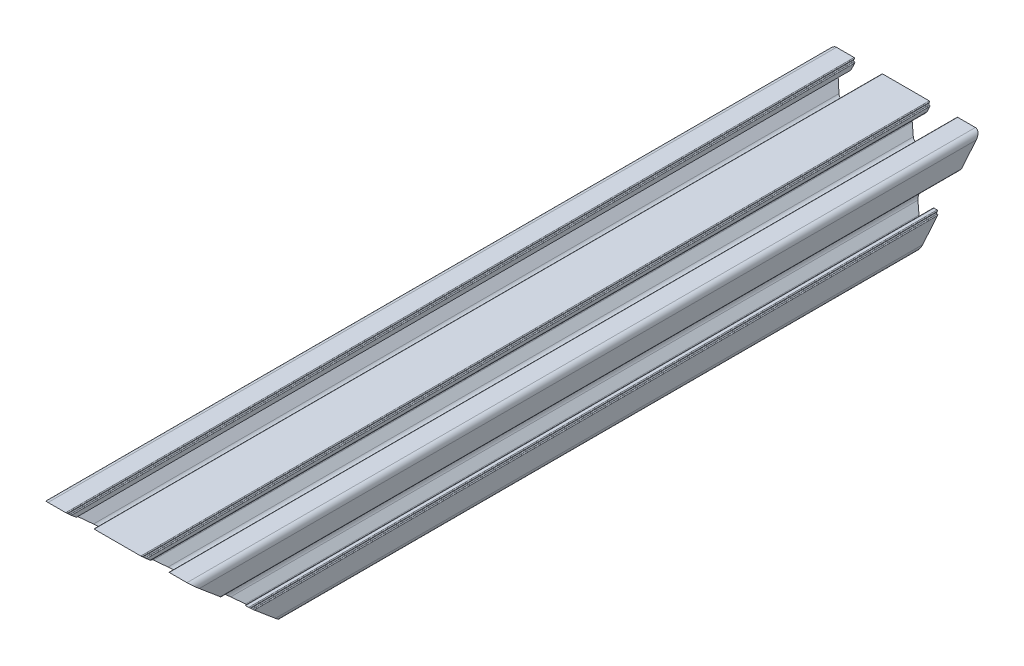
SolidWorks part; units mm, degrees
material "6063-O"
ref_plane "Front Plane" through (0, 0, 0) normal (0, 0, 1) x (1, 0, 0)
ref_plane "Top Plane" through (0, 0, 0) normal (0, 1, 0) x (1, 0, 0)
ref_plane "Right Plane" through (0, 0, 0) normal (1, 0, 0) x (0, 0, -1)
sketch "Sketch1" plane through (0, 0, 0) normal (0, 0, 1) x (1, 0, 0)
  line L0 (1.5, 0) -> (6.2, 0)
  line L1 (40, 1.5) -> (40, 6.2)
  line L2 (38.5, 20) -> (33.8, 20)
  line L3 (0, 18.5) -> (0, 13.8)
  line L4 (17.6, 1.8) -> (22.4, 1.8)
  line L5 (32.218, 13.9) -> (27.782, 13.9)
  line L6 (26.1, 12.218) -> (26.1, 7.782)
  line L7 (17.6, 18.2) -> (22.4, 18.2)
  line L8 (12.218, 13.9) -> (7.9864, 13.9)
  line L9 (6.1, 12.218) -> (6.1, 7.782)
  line L10 (7.782, 6.1) -> (12.218, 6.1)
  line L11 (13.9, 7.782) -> (13.9, 12.218)
  line L12 (27.782, 6.1) -> (32.218, 6.1)
  line L13 (33.9, 7.782) -> (33.9, 12.218)
  line L14 (26.7213, 14.3393) -> (24.9393, 16.1213)
  line L15 (33.2787, 14.3393) -> (35.0607, 16.1213)
  line L16 (34.3393, 13.2787) -> (36.1213, 15.0607)
  line L17 (25.6607, 6.7213) -> (23.1393, 4.2)
  line L18 (15.2, 1.8) -> (13.4, 1.8)
  line L19 (26.7213, 5.6607) -> (24.9393, 3.8787)
  line L20 (24.8, 1.8) -> (26.6, 1.8)
  line L21 (15.3, 18.2) -> (13.1, 18.2)
  line L22 (13.2787, 14.3393) -> (15.1607, 16.2213)
  line L23 (14.3393, 13.2787) -> (16.8607, 15.8)
  line L24 (5.6607, 6.7213) -> (3.8787, 4.9393)
  line L25 (6.7213, 5.6607) -> (4.9393, 3.8787)
  line L26 (6.897, 14.3689) -> (4.9106, 16.4674)
  line L27 (5.6607, 13.2787) -> (3.8787, 15.0607)
  line L28 (14.3393, 6.7213) -> (16.8607, 4.2)
  line L29 (13.2787, 5.6607) -> (15.0607, 3.8787)
  line L30 (24.8, 18.2) -> (26.6, 18.2)
  line L31 (25.6607, 13.2787) -> (23.1393, 15.8)
  line L32 (34.3393, 6.7213) -> (36.1213, 4.9393)
  line L33 (33.2787, 5.6607) -> (35.0607, 3.8787)
  line L34 (1.8, 15.2) -> (1.8, 13.4)
  line L35 (24.5, 2.1) -> (24.5, 2.818)
  line L36 (4.5, 2.1) -> (4.5, 2.818)
  line L37 (2.818, 4.5) -> (2.1, 4.5)
  line L38 (4.5, 17.9) -> (4.5, 17.4986)
  line L39 (2.818, 15.5) -> (2.1, 15.5)
  line L40 (15.6, 17.9) -> (15.6, 17.282)
  line L41 (15.5, 2.818) -> (15.5, 2.1)
  line L42 (38.2, 15.2) -> (38.2, 13.4)
  line L43 (35.5, 2.818) -> (35.5, 2.1)
  line L44 (37.182, 4.5) -> (37.9, 4.5)
  line L45 (35.5, 17.182) -> (35.5, 17.9)
  line L46 (37.182, 15.5) -> (37.9, 15.5)
  line L47 (17.3, 2.1) -> (17.3, 3.1393)
  line L48 (22.7, 2.1) -> (22.7, 3.1393)
  line L49 (17.3, 17.9) -> (17.3, 16.8607)
  line L50 (22.7, 17.9) -> (22.7, 16.8607)
  line L51 (24.5, 17.9) -> (24.5, 17.182)
  line L52 (6.9, 19.3) -> (6.9, 18.2)
  line L53 (13.1, 19.3) -> (13.1, 18.2)
  line L54 (6.9, 1.5) -> (6.9, 0.7)
  line L55 (13.1, 1.5) -> (13.1, 0.7)
  line L56 (13.8, 0) -> (26.2, 0)
  line L57 (6.6, 1.8) -> (4.8, 1.8)
  line L58 (6.9, 18.2) -> (4.8, 18.2)
  line L59 (6.2, 20) -> (1.5, 20)
  line L60 (39.3, 6.9) -> (38.5, 6.9)
  line L61 (39.3, 13.1) -> (38.5, 13.1)
  line L62 (1.5, 13.1) -> (0.7, 13.1)
  line L63 (1.5, 6.9) -> (0.7, 6.9)
  line L64 (0, 6.2) -> (0, 1.5)
  line L65 (1.8, 6.6) -> (1.8, 4.8)
  line L66 (38.2, 6.6) -> (38.2, 4.8)
  line L67 (40, 13.8) -> (40, 18.5)
  line L68 (33.1, 19.3) -> (33.1, 18.5)
  line L69 (26.9, 19.3) -> (26.9, 18.5)
  line L70 (26.9, 1.5) -> (26.9, 0.7)
  line L71 (33.1, 1.5) -> (33.1, 0.7)
  line L72 (33.8, 0) -> (38.5, 0)
  line L73 (33.4, 1.8) -> (35.2, 1.8)
  line L74 (26.2, 20) -> (13.8, 20)
  line L75 (33.4, 18.2) -> (35.2, 18.2)
  line L76 (6.7, 0.5) -> (6.6, 0.5)
  line L77 (6.4, 0.3) -> (6.4, 0.2)
  line L78 (13.3, 0.5) -> (13.4, 0.5)
  line L79 (13.6, 0.3) -> (13.6, 0.2)
  line L80 (26.7, 0.5) -> (26.6, 0.5)
  line L81 (26.4, 0.3) -> (26.4, 0.2)
  line L82 (33.3, 0.5) -> (33.4, 0.5)
  line L83 (33.6, 0.3) -> (33.6, 0.2)
  line L85 (6.4, 19.8) -> (6.4, 19.7)
  line L86 (6.6, 19.5) -> (6.7, 19.5)
  line L87 (13.6, 19.8) -> (13.6, 19.7)
  line L88 (13.4, 19.5) -> (13.3, 19.5)
  line L89 (26.4, 19.8) -> (26.4, 19.7)
  line L90 (26.6, 19.5) -> (26.7, 19.5)
  line L91 (33.6, 19.8) -> (33.6, 19.7)
  line L92 (33.4, 19.5) -> (33.3, 19.5)
  line L93 (0.5, 13.3) -> (0.5, 13.4)
  line L94 (0.3, 13.6) -> (0.2, 13.6)
  line L95 (0.5, 6.7) -> (0.5, 6.6)
  line L96 (0.3, 6.4) -> (0.2, 6.4)
  line L97 (39.5, 13.3) -> (39.5, 13.4)
  line L98 (39.7, 13.6) -> (39.8, 13.6)
  line L99 (39.5, 6.7) -> (39.5, 6.6)
  line L100 (39.7, 6.4) -> (39.8, 6.4)
  circle A0 centre (10, 10) radius 2.5
  circle A1 centre (30, 10) radius 2.5
  arc A2 (38.5, 0) -> (40, 1.5) centre (38.5, 1.5) ccw
  arc A3 (40, 18.5) -> (38.5, 20) centre (38.5, 18.5) ccw
  arc A4 (1.5, 0) -> (0, 1.5) centre (1.5, 1.5) cw
  arc A5 (1.5, 20) -> (0, 18.5) centre (1.5, 18.5) ccw
  arc A6 (26.7213, 5.6607) -> (27.782, 6.1) centre (27.782, 4.6) cw
  arc A7 (32.218, 6.1) -> (33.2787, 5.6607) centre (32.218, 4.6) cw
  arc A8 (33.9, 7.782) -> (34.3393, 6.7213) centre (35.4, 7.782) ccw
  arc A9 (33.2787, 14.3393) -> (32.218, 13.9) centre (32.218, 15.4) cw
  arc A10 (14.3393, 6.7213) -> (13.9, 7.782) centre (15.4, 7.782) cw
  arc A11 (14.3393, 13.2787) -> (13.9, 12.218) centre (15.4, 12.218) ccw
  arc A12 (25.6607, 6.7213) -> (26.1, 7.782) centre (24.6, 7.782) ccw
  arc A13 (26.1, 12.218) -> (25.6607, 13.2787) centre (24.6, 12.218) ccw
  arc A14 (27.782, 13.9) -> (26.7213, 14.3393) centre (27.782, 15.4) cw
  arc A15 (5.6607, 13.2787) -> (6.1, 12.218) centre (4.6, 12.218) cw
  arc A16 (5.6607, 6.7213) -> (6.1, 7.782) centre (4.6, 7.782) ccw
  arc A17 (13.2787, 5.6607) -> (12.218, 6.1) centre (12.218, 4.6) ccw
  arc A18 (6.7213, 5.6607) -> (7.782, 6.1) centre (7.782, 4.6) cw
  arc A19 (13.2787, 14.3393) -> (12.218, 13.9) centre (12.218, 15.4) cw
  arc A20 (6.897, 14.3689) -> (7.9864, 13.9) centre (7.9864, 15.4) ccw
  arc A21 (36.1213, 4.9393) -> (37.182, 4.5) centre (37.182, 6) ccw
  arc A22 (36.1213, 15.0607) -> (37.182, 15.5) centre (37.182, 14) cw
  arc A23 (35.0607, 16.1213) -> (35.5, 17.182) centre (34, 17.182) ccw
  arc A24 (24.5, 17.182) -> (24.9393, 16.1213) centre (26, 17.182) ccw
  arc A25 (22.7, 16.8607) -> (23.1393, 15.8) centre (24.2, 16.8607) ccw
  arc A26 (17.3, 16.8607) -> (16.8607, 15.8) centre (15.8, 16.8607) cw
  arc A27 (4.9106, 16.4674) -> (4.5, 17.4986) centre (6, 17.4986) cw
  arc A28 (15.6, 17.282) -> (15.1607, 16.2213) centre (14.1, 17.282) cw
  arc A29 (3.8787, 15.0607) -> (2.818, 15.5) centre (2.818, 14) ccw
  arc A30 (3.8787, 4.9393) -> (2.818, 4.5) centre (2.818, 6) cw
  arc A31 (4.9393, 3.8787) -> (4.5, 2.818) centre (6, 2.818) ccw
  arc A32 (35.0607, 3.8787) -> (35.5, 2.818) centre (34, 2.818) cw
  arc A33 (24.9393, 3.8787) -> (24.5, 2.818) centre (26, 2.818) ccw
  arc A34 (22.7, 3.1393) -> (23.1393, 4.2) centre (24.2, 3.1393) cw
  arc A35 (17.3, 3.1393) -> (16.8607, 4.2) centre (15.8, 3.1393) ccw
  arc A36 (15.5, 2.818) -> (15.0607, 3.8787) centre (14, 2.818) ccw
  arc A37 (1.8, 6.6) -> (1.5, 6.9) centre (1.5, 6.6) ccw
  arc A38 (1.8, 13.4) -> (1.5, 13.1) centre (1.5, 13.4) cw
  arc A39 (17.6, 18.2) -> (17.3, 17.9) centre (17.6, 17.9) ccw
  arc A40 (22.4, 1.8) -> (22.7, 2.1) centre (22.4, 2.1) ccw
  arc A41 (17.6, 1.8) -> (17.3, 2.1) centre (17.6, 2.1) cw
  arc A42 (15.2, 1.8) -> (15.5, 2.1) centre (15.2, 2.1) ccw
  arc A43 (6.6, 1.8) -> (6.9, 1.5) centre (6.6, 1.5) cw
  arc A44 (13.4, 1.8) -> (13.1, 1.5) centre (13.4, 1.5) ccw
  arc A45 (24.8, 1.8) -> (24.5, 2.1) centre (24.8, 2.1) cw
  arc A46 (35.2, 1.8) -> (35.5, 2.1) centre (35.2, 2.1) ccw
  arc A47 (26.6, 1.8) -> (26.9, 1.5) centre (26.6, 1.5) cw
  arc A48 (33.4, 1.8) -> (33.1, 1.5) centre (33.4, 1.5) ccw
  arc A49 (26.9, 18.5) -> (26.6, 18.2) centre (26.6, 18.5) cw
  arc A50 (33.1, 18.5) -> (33.4, 18.2) centre (33.4, 18.5) ccw
  arc A51 (37.9, 4.5) -> (38.2, 4.8) centre (37.9, 4.8) ccw
  arc A52 (38.5, 13.1) -> (38.2, 13.4) centre (38.5, 13.4) cw
  arc A53 (38.5, 6.9) -> (38.2, 6.6) centre (38.5, 6.6) ccw
  arc A54 (38.2, 15.2) -> (37.9, 15.5) centre (37.9, 15.2) ccw
  arc A55 (35.2, 18.2) -> (35.5, 17.9) centre (35.2, 17.9) cw
  arc A56 (24.8, 18.2) -> (24.5, 17.9) centre (24.8, 17.9) ccw
  arc A57 (22.4, 18.2) -> (22.7, 17.9) centre (22.4, 17.9) cw
  arc A58 (15.3, 18.2) -> (15.6, 17.9) centre (15.3, 17.9) cw
  arc A59 (4.5, 17.9) -> (4.8, 18.2) centre (4.8, 17.9) cw
  arc A60 (1.8, 15.2) -> (2.1, 15.5) centre (2.1, 15.2) cw
  arc A61 (1.8, 4.8) -> (2.1, 4.5) centre (2.1, 4.8) ccw
  arc A62 (4.5, 2.1) -> (4.8, 1.8) centre (4.8, 2.1) ccw
  arc A63 (34.3393, 13.2787) -> (33.9, 12.218) centre (35.4, 12.218) ccw
  arc A64 (6.4, 0.2) -> (6.2, 0) centre (6.2, 0.2) cw
  arc A65 (6.6, 0.5) -> (6.4, 0.3) centre (6.6, 0.3) ccw
  arc A66 (6.7, 0.5) -> (6.9, 0.7) centre (6.7, 0.7) ccw
  arc A67 (13.6, 0.2) -> (13.8, 0) centre (13.8, 0.2) ccw
  arc A68 (13.4, 0.5) -> (13.6, 0.3) centre (13.4, 0.3) cw
  arc A69 (13.3, 0.5) -> (13.1, 0.7) centre (13.3, 0.7) cw
  arc A70 (26.4, 0.2) -> (26.2, 0) centre (26.2, 0.2) cw
  arc A71 (26.6, 0.5) -> (26.4, 0.3) centre (26.6, 0.3) ccw
  arc A72 (26.7, 0.5) -> (26.9, 0.7) centre (26.7, 0.7) ccw
  arc A73 (33.6, 0.2) -> (33.8, 0) centre (33.8, 0.2) ccw
  arc A74 (33.4, 0.5) -> (33.6, 0.3) centre (33.4, 0.3) cw
  arc A75 (33.3, 0.5) -> (33.1, 0.7) centre (33.3, 0.7) cw
  arc A76 (39.8, 6.4) -> (40, 6.2) centre (39.8, 6.2) cw
  arc A77 (39.5, 6.6) -> (39.7, 6.4) centre (39.7, 6.6) ccw
  arc A78 (39.5, 6.7) -> (39.3, 6.9) centre (39.3, 6.7) ccw
  arc A79 (39.5, 13.3) -> (39.3, 13.1) centre (39.3, 13.3) cw
  arc A80 (39.5, 13.4) -> (39.7, 13.6) centre (39.7, 13.4) cw
  arc A81 (39.8, 13.6) -> (40, 13.8) centre (39.8, 13.8) ccw
  arc A82 (33.3, 19.5) -> (33.1, 19.3) centre (33.3, 19.3) ccw
  arc A83 (33.6, 19.7) -> (33.4, 19.5) centre (33.4, 19.7) cw
  arc A84 (33.6, 19.8) -> (33.8, 20) centre (33.8, 19.8) cw
  arc A85 (26.7, 19.5) -> (26.9, 19.3) centre (26.7, 19.3) cw
  arc A86 (26.4, 19.7) -> (26.6, 19.5) centre (26.6, 19.7) ccw
  arc A87 (26.4, 19.8) -> (26.2, 20) centre (26.2, 19.8) ccw
  arc A88 (0.2, 6.4) -> (0, 6.2) centre (0.2, 6.2) ccw
  arc A89 (0.5, 6.6) -> (0.3, 6.4) centre (0.3, 6.6) cw
  arc A90 (0.5, 6.7) -> (0.7, 6.9) centre (0.7, 6.7) cw
  arc A91 (13.3, 19.5) -> (13.1, 19.3) centre (13.3, 19.3) ccw
  arc A92 (13.6, 19.7) -> (13.4, 19.5) centre (13.4, 19.7) cw
  arc A93 (13.6, 19.8) -> (13.8, 20) centre (13.8, 19.8) cw
  arc A94 (6.2, 20) -> (6.4, 19.8) centre (6.2, 19.8) cw
  arc A95 (6.7, 19.5) -> (6.9, 19.3) centre (6.7, 19.3) cw
  arc A96 (6.4, 19.7) -> (6.6, 19.5) centre (6.6, 19.7) ccw
  arc A97 (0.5, 13.3) -> (0.7, 13.1) centre (0.7, 13.3) ccw
  arc A98 (0.2, 13.6) -> (0, 13.8) centre (0.2, 13.8) cw
  arc A99 (0.5, 13.4) -> (0.3, 13.6) centre (0.3, 13.4) ccw
  point P87 (0, 0)
  point P178 (1.8, 6.9)
  point P181 (1.8, 13.1)
  point P186 (22.7, 1.8)
  point P193 (6.9, 1.8)
  point P204 (33.1, 1.8)
  point P209 (33.1, 18.2)
  point P216 (38.2, 6.9)
  point P243 (6.9, 0.5)
  point P248 (13.6, 0.5)
  point P257 (26.9, 0.5)
extrude "Boss-Extrude2" add sketch "Sketch1" along normal blind 400 contours A57 L7 A39 L49 A26 L23 A11 L11 A10 L28 A35 L47 A41 L4 A40 L48 A34 L17 A12 L6 A13 L31 A25 L50 | A0 | A1 | L59 A5 L3 A98 L94 A99 L93 A97 L62 A38 L34 A60 L39 A29 L27 A15 L9 A16 L24 A30 L37 A61 L65 A37 L63 A90 L95 A89 L96 A88 L64 A4 L0 A64 L77 A65 L76 A66 L54 A43 L57 A62 L36 A31 L25 A18 L10 A17 L29 A36 L41 A42 L18 A44 L55 A69 L78 A68 L79 A67 L56 A70 L81 A71 L80 A72 L70 A47 L20 A45 L35 A33 L19 A6 L12 A7 L33 A32 L43 A46 L73 A48 L71 A75 L82 A74 L83 A73 L72 A2 L1 A76 L100 A77 L99 A78 L60 A53 L66 A51 L44 A21 L32 A8 L13 A63 L16 A22 L46 A54 L42 A52 L61 A79 L97 A80 L98 A81 L67 A3 L2 A84 L91 A83 L92 A82 L68 A50 L75 A55 L45 A23 L15 A9 L5 A14 L14 A24 L51 A56 L30 A49 L69 A85 L90 A86 L89 A87 L74 A93 L87 A92 L88 A91 L53 L21 A58 L40 A28 L22 A19 L8 A20 L26 A27 L38 A59 L58 L52 A95 L86 A96 L85 A94
sketch "Sketch4" plane through (40, 0, 0) normal (1, 0, 0) x (0, 0, -1)
  line L0 (-341.2215, 20) -> (-131.2215, 20)
  line L1 (-400, 20) -> (0, 20) construction
  line L2 (-131.2215, 20) -> (-148.0035, 0)
  line L3 (-400, 0) -> (0, 0) construction
  line L4 (-148.0035, 0) -> (-317.3865, 0)
  line L6 (-317.3865, 0) -> (-341.2215, 20)
  line L7 (-341.2215, 20) -> (-358.5281, 43.0882)
  line L8 (-358.5281, 43.0882) -> (-373.2484, 40.9548)
  line L9 (-373.2484, 40.9548) -> (-418.0061, 34.4682)
  line L10 (-131.2215, 20) -> (-112.5209, 51.8254)
  line L11 (-112.5209, 51.8254) -> (-58.9711, 72.2254)
  line L12 (-58.9711, 72.2254) -> (9.4537, 62.0254)
  line L13 (-418.0061, 34.4682) -> (-410.9476, -14.2352)
  line L14 (-410.9476, -14.2352) -> (-349.8748, -23.6868)
  line L15 (-349.8748, -23.6868) -> (-317.3865, 0)
  line L16 (9.4537, 62.0254) -> (39.2036, -8.5244)
  line L17 (39.2036, -8.5244) -> (-4.9963, -57.8242)
  line L18 (-4.9963, -57.8242) -> (-140.9958, -57.8242)
  line L19 (-140.9958, -57.8242) -> (-140.9958, -14.2352)
  line L20 (-140.9958, -14.2352) -> (-148.0035, 0)
  line M5 (0, 13.8) -> (0, 18.5)
  line M6 (0, 18.5) -> (-400, 18.5)
  line M7 (-400, 18.5) -> (-400, 13.8)
  line M8 (-400, 13.8) -> (0, 13.8)
  dimension "D1" = 210
  dimension "D2" = 130
  dimension "D3" = 140
extrude "Cut-Extrude1" cut sketch "Sketch4" against normal blind 90 contours L20 L19 L18 L17 L16 L12 L11 L10 L2 M6 M5 M8 | L14 L15 L6 L7 L8 L9 L13 M8 M7 M6 | L6 M8 M6 M7 | L2 M6 M8 M5
